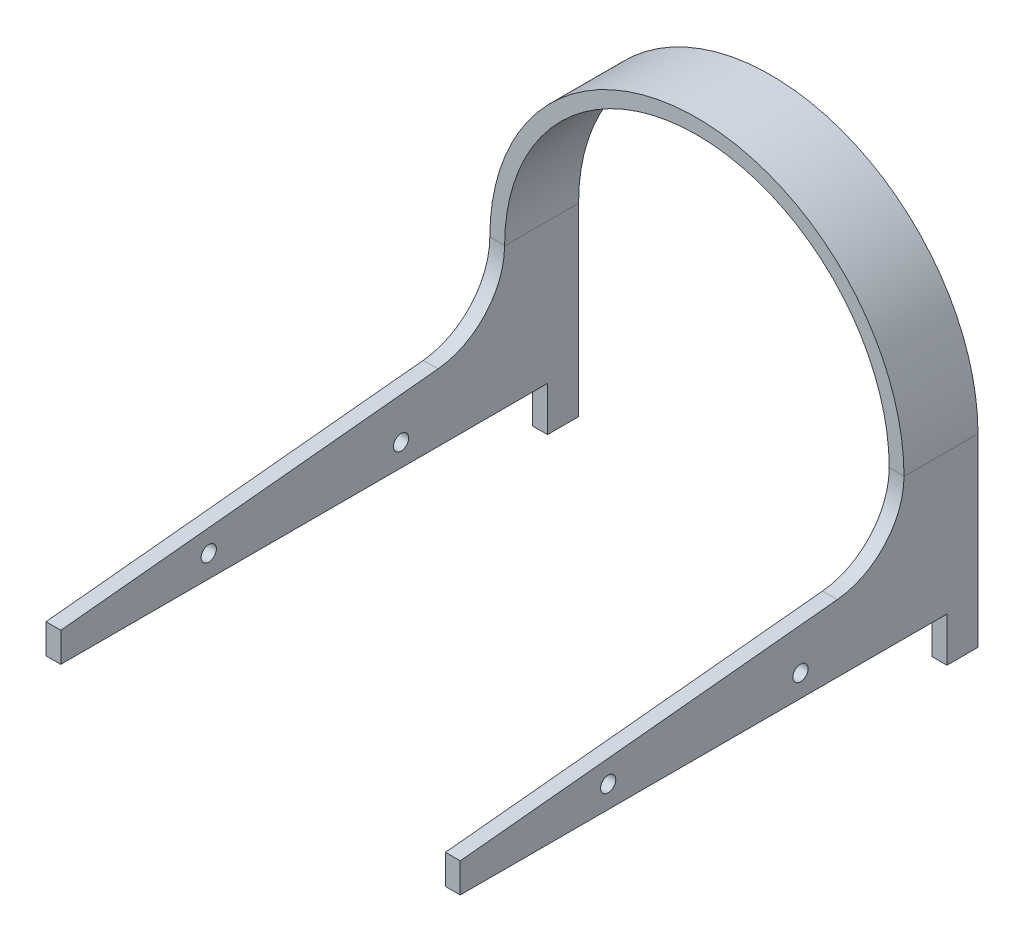
SolidWorks part; units mm, degrees
ref_plane "前视基准面" through (0, 0, 0) normal (0, 0, 1) x (1, 0, 0)
ref_plane "上视基准面" through (0, 0, 0) normal (0, 1, 0) x (1, 0, 0)
ref_plane "右视基准面" through (0, 0, 0) normal (1, 0, 0) x (0, 0, -1)
sketch "草图1" plane through (0, 0, 0) normal (0, 0, 1) x (1, 0, 0)
  line L0 (0, 0) -> (-215.2903, 0) construction
  line L1 (-140, 0) -> (-140, -125)
  line L2 (-140, -125) -> (-130, -125)
  line L3 (-130, -125) -> (-130, 0)
  line L4 (0, 0) -> (0, 101.3952) construction
  line L5 (130, -125) -> (130, 0)
  line L6 (140, -125) -> (130, -125)
  line L7 (140, 0) -> (140, -125)
  arc A0 (130, 0) -> (-130, 0) centre (0, 0) ccw
  arc A1 (140, 0) -> (-140, 0) centre (0, 0) ccw
  dimension "D1" = 260
  dimension "D2" = 280
  dimension "D3" = 125
extrude "凸台-拉伸1" add sketch "草图1" along normal blind 350
sketch "草图2" plane through (-140, 0, 0) normal (-1, 0, 0) x (0, 0, 1)
  line L0 (0, 0) -> (0, -125) construction
  line L1 (350, -125) -> (21, -125)
  line L2 (350, -125) -> (350, -95)
  line L3 (350, -95) -> (21, -95)
  line L4 (21, -125) -> (21, -95)
  line L5 (50, 140) -> (50, 0.2494)
  line L6 (350, 140) -> (0, 140) construction
  line L7 (95.0248, -49.5025) -> (350, -75)
  line L8 (350, 0) -> (350, -125) construction
  line L9 (350, -75) -> (350, 140)
  line L10 (350, 140) -> (50, 140)
  line L11 (0, 140) -> (0, 0) construction
  arc A0 (50, 0.2494) -> (95.0248, -49.5025) centre (100, 0.2494) ccw
  point P20 (50, -45)
  dimension "D6" = 50
  dimension "D1" = 30
  dimension "D2" = 21
  dimension "D3" = 50
  dimension "D4" = 185
  dimension "D5" = 20
extrude "切除-拉伸1" cut sketch "草图2" against normal through all
sketch "草图3" plane through (-140, 0, 0) normal (-1, 0, 0) x (0, 0, 1)
  line L0 (350, -75) -> (350, -95) construction
  line L1 (350, -95) -> (21, -95) construction
  circle A0 centre (120, -80) radius 5.15
  circle A1 centre (250, -80) radius 5.15
  point P4 (0, 0)
  point P7 (0, 0)
  dimension "D1" = 130
  dimension "D2" = 100
  dimension "D3" = 10.3
  dimension "D4" = 10.3
  dimension "D5" = 15
extrude "切除-拉伸2" cut sketch "草图3" against normal through all
